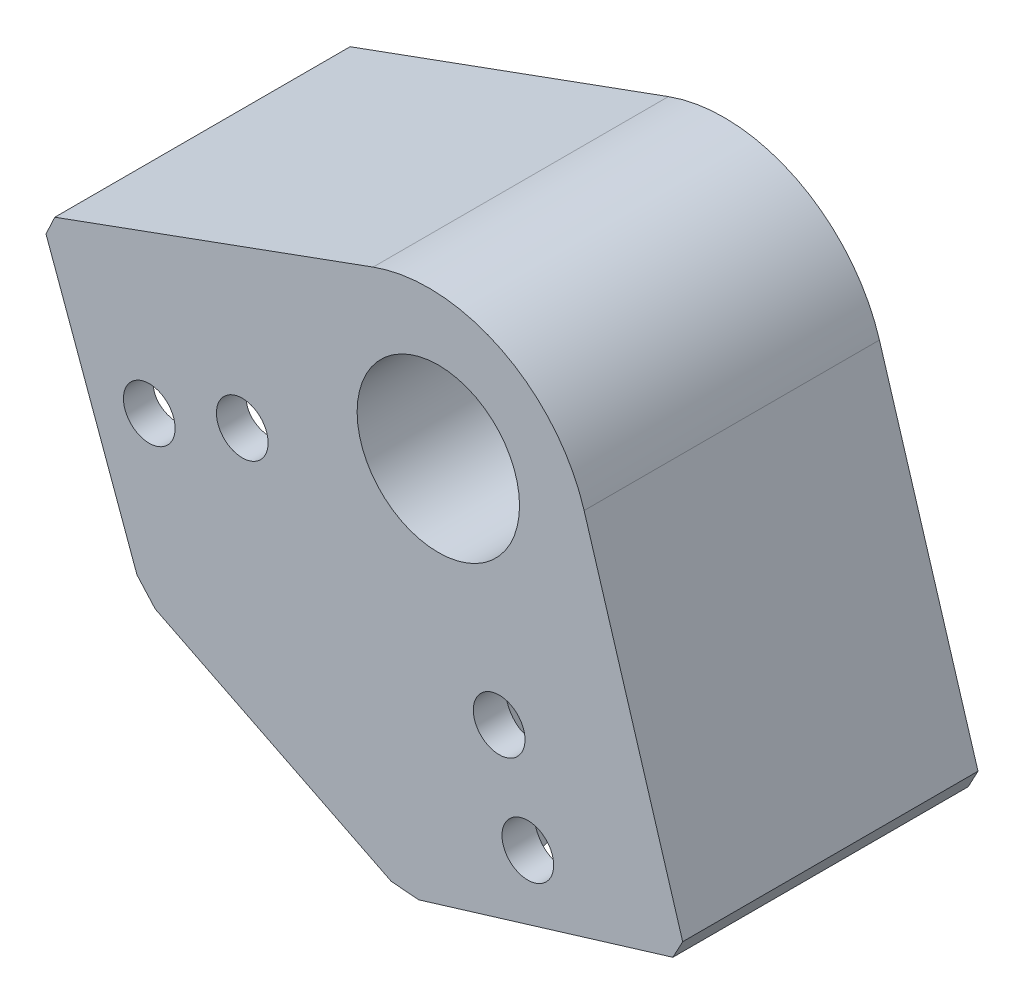
SolidWorks part; units mm, degrees
ref_plane "Front Plane" through (0, 0, 0) normal (0, 0, 1) x (1, 0, 0)
ref_plane "Top Plane" through (0, 0, 0) normal (0, 1, 0) x (1, 0, 0)
ref_plane "Right Plane" through (0, 0, 0) normal (1, 0, 0) x (0, 0, -1)
sketch "Sketch1" plane through (0, 0, 0) normal (0, 0, 1) x (1, 0, 0)
  line L0 (0, 0) -> (14549.1217, -47836.4198) construction
  line L1 (0, 0) -> (-46979.6201, -17114.7683) construction
  line L2 (-53.8255, 1.6771) -> (-40.1337, -35.9066)
  line L3 (-4.5854, -53.6561) -> (33.6837, -42.0168)
  line L4 (-40.1337, -35.9066) -> (-4.5854, -53.6561)
  line L5 (-53.8255, 1.6771) -> (33.6837, -42.0168)
  line L6 (-53.8255, 1.6771) -> (33.6837, -42.0168)
  line L7 (-53.8255, 1.6771) -> (-40.424, 28.5173)
  line L8 (33.6837, -42.0168) -> (47.0852, -15.1765)
  line L9 (-40.424, 28.5173) -> (47.0852, -15.1765)
  point P8 (-46.9796, -17.1148)
  point P11 (14.5491, -47.8364)
  dimension "D1" = 86.9
  dimension "D2" = 40
  dimension "D3" = 40
  dimension "D4" = 50
  dimension "D5" = 50
  dimension "D6" = 30
extrude "Boss-Extrude1" add sketch "Sketch1" along normal blind 40 contours L9 L7 L5 L8 | L5 L2 L4 L3
sketch "Sketch2" plane through (14.5491, -47.8364, 0) normal (0.291, -0.9567, 0) x (-0.9567, -0.291, 0)
  line L0 (20, -40) -> (-20, -40) construction
  line L2 (20, -40) -> (20, 0) construction
  circle A0 centre (0, -20) radius 16
  dimension "D1" = 32
  dimension "D2" = 20
  dimension "D3" = 20
extrude "Cut-Extrude1" cut sketch "Sketch2" against normal blind 30
sketch "Sketch3" plane through (-46.9796, -17.1148, 0) normal (-0.9396, -0.3423, 0) x (0, 0, 1)
  line L0 (40, 20) -> (0, 20) construction
  line L1 (40, 20) -> (40, -20) construction
  circle A0 centre (20, 0) radius 16
  dimension "D1" = 32
  dimension "D2" = 20
  dimension "D3" = 20
extrude "Cut-Extrude2" cut sketch "Sketch3" against normal blind 30
sketch "Sketch4" plane through (0, 0, 0) normal (0, 0, -1) x (-1, 0, 0)
  line L0 (-29.8568, -43.1807) -> (-21.125, -14.4713) construction
  line L1 (-21.125, -14.4713) -> (9.358, -23.7425) construction
  line L2 (52.4563, -2.0813) -> (24.205, 8.2107) construction
  line L3 (24.205, 8.2107) -> (13.2411, -21.8849) construction
  line L4 (4.5854, -53.6561) -> (-33.6837, -42.0168) construction
  line L5 (53.8255, 1.6771) -> (40.1337, -35.9066) construction
  circle A0 centre (-8.2412, -27.0966) radius 3.5
  circle A1 centre (-12.1252, -39.8669) radius 3.5
  circle A2 centre (26.5551, -9.6741) radius 3.5
  circle A3 centre (39.1528, -14.2634) radius 3.5
  dimension "D1" = 7
  dimension "D2" = 7
  dimension "D3" = 7
  dimension "D4" = 7
  dimension "D5" = 16
  dimension "D7" = 8.33
  dimension "D9" = 16
  dimension "D10" = 16
  dimension "D11" = 8.33
  dimension "D12" = 8.33
  dimension "D6" = 16
  dimension "D8" = 8.33
extrude "Cut-Extrude3" cut sketch "Sketch4" against normal up to surface (40 mm away) up to face at (-9.7, -19.4269, 40)
sketch "Sketch5" plane through (0, 0, 0) normal (0, 0, -1) x (-1, 0, 0)
  line L0 (46.9796, -17.1148) -> (47026.5997, -17131.8831) construction
  line L1 (53.8255, 1.6771) -> (40.1337, -35.9066) construction
  line L2 (-14.5491, -47.8364) -> (14534.5726, 47788.5834) construction
  line L3 (4.5854, -53.6561) -> (-33.6837, -42.0168) construction
  circle A0 centre (0, 0) radius 11
  point P6 (46.9796, -17.1148)
  point P11 (-14.5491, -47.8364)
  point P12 (0, 0)
  dimension "D1" = 22
sketch "Sketch6" plane through (3.3306, 6.6704, 0) normal (0.4467, 0.8947, 0) x (0.8947, -0.4467, 0)
  line L1 (-48.9056, 0) -> (48.9056, 0)
  line L2 (-48.9056, 0) -> (-48.9056, -40)
  line L3 (-48.9056, -40) -> (48.9056, -40)
  line L4 (48.9056, 0) -> (48.9056, -40)
  line L5 (0, -40) -> (0, 0) construction
  line L6 (-48.9056, -20) -> (48.9056, -20) construction
  point P152 (0, -20)
extrude "Boss-Extrude2" add sketch "Sketch6" along normal blind 30
extrude "Cut-Extrude4" cut sketch "Sketch5" against normal up to surface (40 mm away) contours A0 up to face at (-35.6528, -14.2634, 40)
sketch "Sketch7" plane through (0, 0, 0) normal (0, 0, -1) x (-1, 0, 0)
  line L0 (-33.6837, -42.0168) -> (-9.6347, 37.0544)
  line L1 (-60.4867, 11.6638) -> (27.0225, 55.3576) construction
  line L2 (53.8255, 1.6771) -> (-23.8294, 29.9669)
  line L3 (53.8255, 1.6771) -> (40.1337, -35.9066) construction
  line L4 (4.5854, -53.6561) -> (-33.6837, -42.0168) construction
  line L5 (53.8255, 1.6771) -> (27.0225, 55.3576)
  line L7 (27.0225, 55.3576) -> (-60.4867, 11.6638)
  line L8 (-60.4867, 11.6638) -> (-33.6837, -42.0168)
  line M9 (53.8255, 1.6771) -> (27.0225, 55.3576)
  line M10 (27.0225, 55.3576) -> (-60.4867, 11.6638)
  line M11 (-60.4867, 11.6638) -> (-33.6837, -42.0168)
extrude "Cut-Extrude7" cut sketch "Sketch7" against normal up to surface (40 mm away) contours L0 L2 M10 M11 | L2 L0 M10 | L2 L0 M9 M10 up to face at (11, 0, 40)
fillet "Fillet1" radius 22 1 edges at (12.9912, 26.0185, 20)
chamfer "Chamfer1" distance 2 angle 45 2 edges at (33.6837, -42.0168, 20) (-53.8255, 1.6771, 20)
chamfer "Chamfer2" distance 2 2 edges at (-40.1337, -35.9066, 20) (-4.5854, -53.6561, 20)
